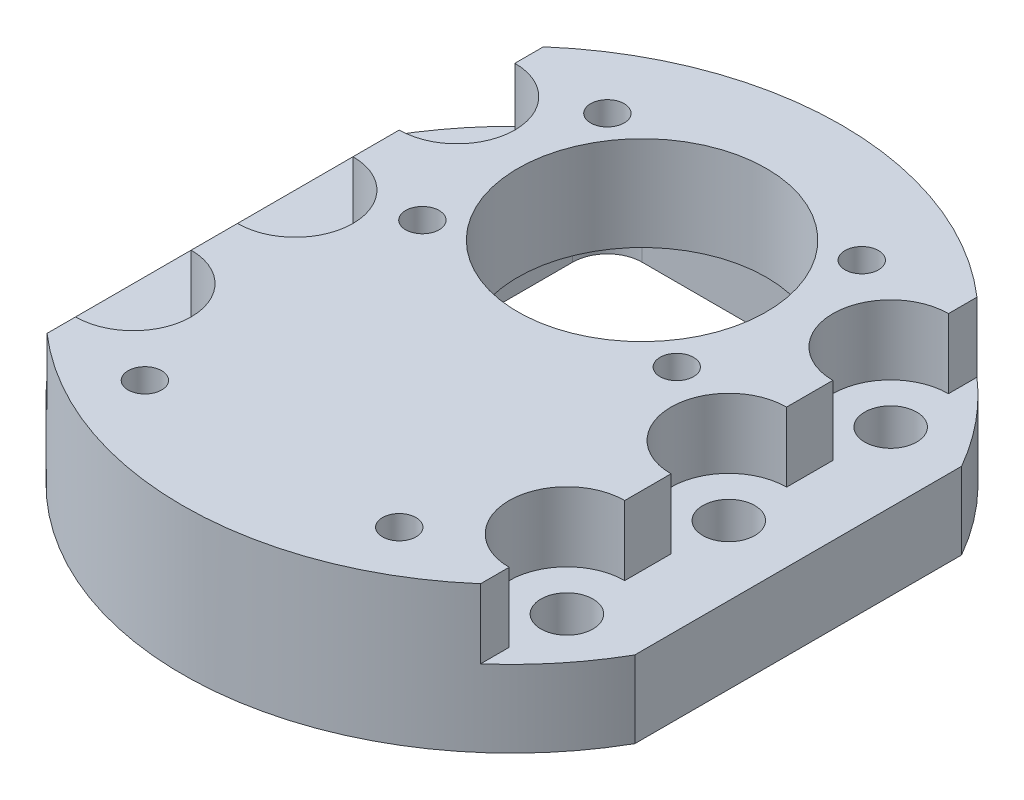
SolidWorks part; units mm, degrees
material "POM generico"
ref_plane "Piano frontale" through (0, 0, 0) normal (0, 0, 1) x (1, 0, 0)
ref_plane "Piano superiore" through (0, 0, 0) normal (0, 1, 0) x (1, 0, 0)
ref_plane "Piano destro" through (0, 0, 0) normal (1, 0, 0) x (0, 0, -1)
sketch "Schizzo1" plane through (0, 0, 0) normal (0, 1, 0) x (1, 0, 0)
  line L0 (-14, 8) -> (-14, -8)
  line L1 (-11, 11) -> (0, 11)
  line L2 (-11, -11) -> (0, -11)
  line L3 (0, 11) -> (0, -11) construction
  line L4 (11, -11) -> (0, -11)
  line L5 (11, 11) -> (0, 11)
  line L6 (14, 8) -> (14, -8)
  circle A0 centre (0, 0) radius 11 construction
  circle A1 centre (-11, 8) radius 3 construction
  circle A2 centre (-11, -8) radius 3 construction
  circle A3 centre (-11, -32) radius 3
  arc A4 (-14, 8) -> (-11, 11) centre (-11, 8) cw
  arc A5 (-14, -8) -> (-11, -11) centre (-11, -8) ccw
  circle A6 centre (11, -8) radius 3 construction
  circle A7 centre (11, 8) radius 3 construction
  arc A8 (14, -8) -> (11, -11) centre (11, -8) cw
  arc A9 (14, 8) -> (11, 11) centre (11, 8) ccw
  circle A10 centre (11, -32) radius 3
  dimension "D1" = 22
  dimension "D2" = 6
  dimension "D3" = 11
  dimension "D4" = 8
  dimension "D5" = 8
  dimension "D6" = 40
sketch "Schizzo3" plane through (0, 0, 0) normal (0, 1, 0) x (1, 0, 0)
  line L0 (-24.75, 2.8811) -> (-24.75, -25.3811)
  line L1 (14.25, -34.5) -> (-14.25, -34.5) construction
  line L2 (14.25, -34.5) -> (14.25, 12) construction
  line L3 (14.25, 12) -> (-14.25, 12) construction
  line L4 (-14.25, -34.5) -> (-14.25, 12) construction
  line L5 (14.25, -34.5) -> (-14.25, 12) construction
  line L6 (14.25, 12) -> (-14.25, -34.5) construction
  line L7 (24.75, 2.8811) -> (24.75, -25.3811)
  line L9 (-24.25, -11.25) -> (24.25, -11.25) construction
  line L10 (0, -36.5) -> (0, 14) construction
  line L13 (14.25, -34.5) -> (-14.25, -34.5) construction
  circle A0 centre (-18.75, 2.75) radius 3.5 construction
  circle A1 centre (-18.75, 2.75) radius 2.25
  circle A2 centre (18.75, 2.75) radius 3.5 construction
  circle A3 centre (18.75, 2.75) radius 2.25
  circle A4 centre (18.75, -25.25) radius 3.5 construction
  circle A5 centre (-18.75, -25.25) radius 3.5 construction
  circle A6 centre (18.75, -25.25) radius 2.25
  circle A7 centre (-18.75, -25.25) radius 2.25
  circle A8 centre (-18.75, -11.25) radius 2.25
  circle A9 centre (18.75, -11.25) radius 2.25
  circle A10 centre (0, -11.25) radius 28.5 construction
  arc A11 (-24.75, 2.8811) -> (24.75, 2.8811) centre (0, -11.25) cw
  arc A12 (-24.75, -25.3811) -> (24.75, -25.3811) centre (0, -11.25) ccw
  point P0 (0, -11.25)
  point P25 (0, -11.25)
  dimension "D4" = 7
  dimension "D5" = 4.5
  dimension "D7" = 57
  dimension "D1" = 28.5
  dimension "D2" = 46.5
  dimension "D3" = 11.25
  dimension "D6" = 4.5
  dimension "D8" = 14
  dimension "D9" = 6
  dimension "D10" = 6
extrude "Estrusione-Estrusione1" add sketch "Schizzo3" along normal blind 12.65
extrude "Taglio-Estrusione1" cut sketch "Schizzo1" along normal blind 4.5
sketch "Schizzo4" plane through (0, 4.5, 0) normal (0, -1, 0) x (1, 0, 0)
  circle A0 centre (0, 0) radius 10.75
  circle A1 centre (-11, 8) radius 1.45
  circle A3 centre (-11, -8) radius 1.45
  circle A4 centre (11, -8) radius 1.45
  circle A5 centre (11, 8) radius 1.45
  circle A6 centre (-11, 32) radius 1.45
  circle A7 centre (11, 32) radius 1.45
  arc A11 (11, -11) -> (14, -8) centre (11, -8) ccw construction
  arc A12 (14, 8) -> (11, 11) centre (11, 8) ccw construction
  circle A13 centre (-11, 32) radius 3 construction
  circle A14 centre (11, 32) radius 3 construction
  arc A15 (-11, 11) -> (-14, 8) centre (-11, 8) ccw construction
  arc A16 (-14, -8) -> (-11, -11) centre (-11, -8) ccw construction
  dimension "D1" = 21.5
  dimension "D2" = 2.9
extrude "Taglio-Estrusione2" cut sketch "Schizzo4" against normal through all
sketch "Schizzo6" plane through (0, 12.65, 0) normal (0, 1, 0) x (1, 0, 0)
  circle A0 centre (-18.75, 2.75) radius 5
  circle A1 centre (-18.75, -11.25) radius 2.25 construction
  circle A2 centre (-18.75, -11.25) radius 5
  circle A3 centre (-18.75, -25.25) radius 5
  circle A4 centre (18.75, -25.25) radius 5
  circle A5 centre (18.75, -11.25) radius 5
  circle A6 centre (18.75, 2.75) radius 5
  circle A7 centre (-18.75, 2.75) radius 2.25 construction
  dimension "D1" = 10
extrude "Taglio-Estrusione3" cut sketch "Schizzo6" against normal blind 6
sketch "Schizzo7" plane through (0, 12.65, 0) normal (0, 1, 0) x (1, 0, 0)
  line L0 (-24.75, 2.8811) -> (-24.75, -25.3811) construction
  line L1 (-34.75, 27.25) -> (-18.75, 27.25)
  line L2 (-34.75, 27.25) -> (-34.75, -49.75)
  line L3 (-34.75, -49.75) -> (-18.75, -49.75)
  line L4 (-18.75, 27.25) -> (-18.75, -49.75)
  line L5 (0, 0) -> (0, 10.75) construction
  line L6 (18.75, 27.25) -> (18.75, -49.75)
  line L7 (34.75, -49.75) -> (18.75, -49.75)
  line L8 (34.75, 27.25) -> (34.75, -49.75)
  line L9 (34.75, 27.25) -> (18.75, 27.25)
  arc A0 (24.75, 2.8811) -> (-24.75, 2.8811) centre (0, -11.25) ccw construction
  arc A1 (-24.75, -25.3811) -> (24.75, -25.3811) centre (0, -11.25) ccw construction
  circle A2 centre (0, 0) radius 10.75 construction
  point P4 (-18.75, 2.75)
  point P9 (0, 17.25)
  point P10 (0, -39.75)
  point P26 (18.75, 2.75)
  dimension "D1" = 10
  dimension "D2" = 10
  dimension "D3" = 10
extrude "Taglio-Estrusione4" cut sketch "Schizzo7" against normal up to surface (6 mm away) up to face at (-18.75, 6.65, -0.5)
